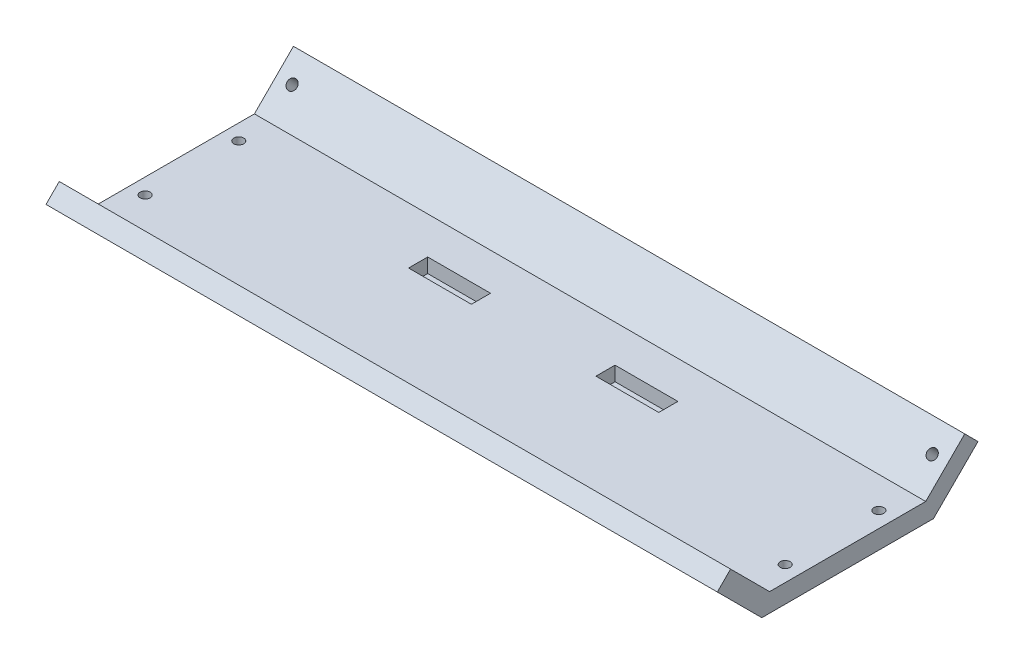
SolidWorks part; units mm, degrees
ref_plane "Front Plane" through (0, 0, 0) normal (0, 0, 1) x (1, 0, 0)
ref_plane "Top Plane" through (0, 0, 0) normal (0, 1, 0) x (1, 0, 0)
ref_plane "Right Plane" through (0, 0, 0) normal (1, 0, 0) x (0, 0, -1)
sketch "Sketch2" plane through (0, 0, 0) normal (1, 0, 0) x (0, 0, -1)
  line L0 (-25, 0) -> (25, 0)
  line L1 (25, 0) -> (37.5, 12.5)
  line L2 (-25, 0) -> (-37.5, 12.5)
  line L8 (27.4853, -6) -> (41.7426, 8.2574)
  line L9 (-27.4853, -6) -> (27.4853, -6)
  line L10 (-27.4853, -6) -> (-41.7426, 8.2574)
  line L11 (-37.5, 12.5) -> (-41.7426, 8.2574)
  line L12 (37.5, 12.5) -> (41.7426, 8.2574)
  line L13 (-37.5, 12.5) -> (-50, 25) construction
  line L14 (37.5, 12.5) -> (50, 25) construction
  point P4 (0, 0)
  dimension "D2" = 135
  dimension "D3" = 135
  dimension "D1" = 100
  dimension "D4" = 25
  dimension "D5" = 6
extrude "Main" add sketch "Sketch2" along normal mid plane 215
hole_wizard "Ø4.0mm Dowel Hole2" positions "3DSketch2" profile "Sketch4" hole size "Ø4.0" standard "ANSI Metric" end condition through all
sketch3d "3DSketch2"
  line L2 (107.5, 0, -25) -> (-107.5, 0, -25) construction
  line L3 (-102.5, 0, -25) -> (-102.5, 0, -15) construction
  line L4 (-102.5, 0, -15) -> (-102.5, 0, 15) construction
  line L5 (-102.5, 0, 15) -> (-102.5, 0, 25) construction
  line L6 (107.5, 0, 25) -> (-107.5, 0, 25) construction
  line L11 (102.5, 0, -25) -> (102.5, 0, -15) construction
  line L12 (102.5, 0, -15) -> (102.5, 0, 15) construction
  line L13 (102.5, 0, 15) -> (102.5, 0, 25) construction
  line L27 (102.5, 0, -25) -> (102.5, 7.0711, -32.0711) construction
  line L29 (102.5, 0, 25) -> (102.5, 7.0711, 32.0711) construction
  line L31 (-102.5, 7.0711, 32.0711) -> (-102.5, 0, 25) construction
  line L35 (-102.5, 7.0711, -32.0711) -> (-107.5, 7.0711, -32.0711) construction
  line L36 (-107.5, 12.5, -37.5) -> (-107.5, 0, -25) construction
  line L38 (-102.5, 7.0711, 32.0711) -> (-107.5, 7.0711, 32.0711) construction
  line L39 (-107.5, 0, 25) -> (-107.5, 12.5, 37.5) construction
  line L41 (102.5, 7.0711, -32.0711) -> (107.5, 7.0711, -32.0711) construction
  line L42 (107.5, 12.5, -37.5) -> (107.5, 0, -25) construction
  line L44 (102.5, 7.0711, 32.0711) -> (107.5, 7.0711, 32.0711) construction
  line L45 (107.5, 0, 25) -> (107.5, 12.5, 37.5) construction
  line L47 (102.5, 0, 25) -> (107.5, 0, 25) construction
  line L49 (-102.5, 0, 25) -> (-107.5, 0, 25) construction
  line L51 (-102.5, 7.0711, -32.0711) -> (-102.5, 0, -25) construction
  point P0 (-102.5, 7.0711, -32.0711)
  point P2 (-102.5, 0, -15)
  point P4 (-102.5, 0, 15)
  point P6 (-102.5, 7.0711, 32.0711)
  point P8 (102.5, 7.0711, 32.0711)
  point P10 (102.5, 0, 15)
  point P12 (102.5, 0, -15)
  point P14 (102.5, 7.0711, -32.0711)
  dimension "D1" = 5
  dimension "D2" = 10
  dimension "D3" = 10
sketch "Sketch4" plane through (-102.5, 7.0711, -32.0711) normal (1, 0, 0) x (0, -0.7071, 0.7071)
  line L0 (0, 0) -> (0, 16.0815)
  line L1 (0, 16.0815) -> (1.6, 16.0815)
  line L2 (1.6, 16.0815) -> (1.6, 0)
  line L5 (1.6, 0) -> (0, 0)
  line L11 (0, -6.35) -> (0, 107.95) construction
  dimension "Thru Hole Dia." = 3.2
  dimension "Thru Hole Depth" = 16.0815
sketch "Sketch5" plane through (0, 0, 0) normal (0, 1, 0) x (1, 0, 0)
  line L1 (-33.5, 21) -> (33.5, 21) construction
  line L2 (-33.5, 21) -> (-33.5, -21) construction
  line L3 (-33.5, -21) -> (33.5, -21) construction
  line L4 (33.5, 21) -> (33.5, -21) construction
  line L5 (-33.5, 21) -> (33.5, -21) construction
  line L6 (-33.5, -21) -> (33.5, 21) construction
  circle A0 centre (-33.5, 21) radius 3.5
  circle A1 centre (33.5, 21) radius 3.5
  circle A2 centre (-33.5, -21) radius 3.5
  circle A3 centre (33.5, -21) radius 3.5
  circle A4 centre (-33.5, 21) radius 1.55
  circle A5 centre (33.5, 21) radius 1.55
  circle A6 centre (33.5, -21) radius 1.55
  circle A7 centre (-33.5, -21) radius 1.55
  point P0 (0, 0)
  dimension "D1" = 7
  dimension "D2" = 3.1
  dimension "D3" = 42
  dimension "D4" = 67
extrude "Boss-Extrude1" [suppressed] add sketch "Sketch5" along normal blind 12
sketch "Sketch6" plane through (0, 0, 0) normal (0, 1, 0) x (1, 0, 0)
  line L0 (0, 0) -> (0, 10) construction
  line L1 (19.9375, 13.0625) -> (40.0625, 13.0625)
  line L2 (19.9375, 13.0625) -> (19.9375, 6.9375)
  line L3 (19.9375, 6.9375) -> (40.0625, 6.9375)
  line L4 (40.0625, 13.0625) -> (40.0625, 6.9375)
  line L5 (19.9375, 13.0625) -> (40.0625, 6.9375) construction
  line L6 (19.9375, 6.9375) -> (40.0625, 13.0625) construction
  line L7 (30, 10) -> (0, 10) construction
  line L8 (-40.0625, 13.0625) -> (-19.9375, 13.0625)
  line L9 (-40.0625, 13.0625) -> (-40.0625, 6.9375)
  line L10 (-40.0625, 6.9375) -> (-19.9375, 6.9375)
  line L11 (-19.9375, 13.0625) -> (-19.9375, 6.9375)
  line L12 (-40.0625, 13.0625) -> (-19.9375, 6.9375) construction
  line L13 (-40.0625, 6.9375) -> (-19.9375, 13.0625) construction
  line L14 (0, 10) -> (-30, 10) construction
  point P0 (30, 10)
  point P5 (-30, 10)
  dimension "D1" = 80.125
  dimension "D2" = 6.125
  dimension "D3" = 39.875
  dimension "D4" = 10
extrude "Shelf cut" cut sketch "Sketch6" against normal through all
sketch "Sketch7" plane through (0, -6, 0) normal (0, -1, 0) x (1, 0, 0)
  line L1 (40.0625, -13.0625) -> (19.9375, -13.0625)
  line L2 (40.0625, -13.0625) -> (40.0625, -6.9375)
  line L3 (40.0625, -6.9375) -> (19.9375, -6.9375)
  line L4 (19.9375, -13.0625) -> (19.9375, -6.9375)
  line L5 (-19.9375, -13.0625) -> (-40.0625, -13.0625)
  line L6 (-19.9375, -13.0625) -> (-19.9375, -6.9375)
  line L7 (-19.9375, -6.9375) -> (-40.0625, -6.9375)
  line L8 (-40.0625, -13.0625) -> (-40.0625, -6.9375)
extrude "Boss-Extrude2" add sketch "Sketch7" against normal blind 1.4
equation "\"length\" = 215mm"
equation "\"D1@Main\" = \"length\""
equation "\"width\" = 220mm"
equation "\"height\" = 100mm"
equation "\"skin_th\" = 6mm"
equation "\"D5@Sketch2\"=\"skin_th\""
equation "\"D1@Sketch2\"=\"height\""
equation "\"shelf_height\" = 10mm"
equation "\"D4@Sketch6\"=\"shelf_height\""
